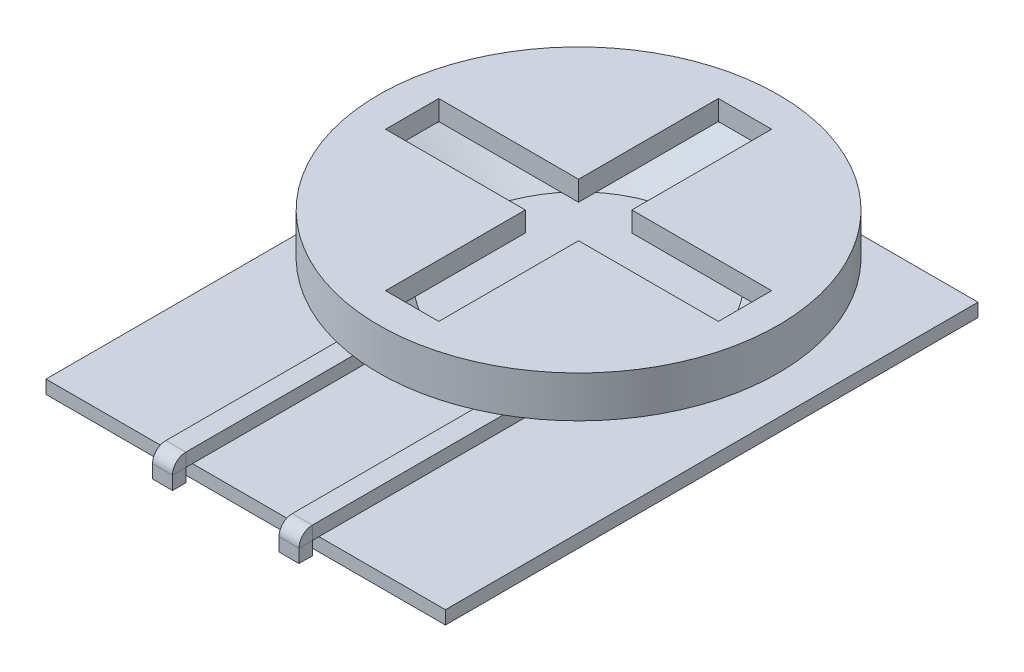
SolidWorks part; units mm, degrees
ref_plane "Front Plane" through (0, 0, 0) normal (0, 0, 1) x (1, 0, 0)
ref_plane "Top Plane" through (0, 0, 0) normal (0, 1, 0) x (1, 0, 0)
ref_plane "Right Plane" through (0, 0, 0) normal (1, 0, 0) x (0, 0, -1)
sketch "Sketch2" plane through (0, 0, 0) normal (0, 1, 0) x (1, 0, 0)
  line L1 (-1.5, 2) -> (1.5, 2)
  line L2 (-1.5, 2) -> (-1.5, -2)
  line L3 (-1.5, -2) -> (1.5, -2)
  line L4 (1.5, 2) -> (1.5, -2)
  line L5 (-1.5, 2) -> (1.5, -2) construction
  line L6 (-1.5, -2) -> (1.5, 2) construction
  point P0 (0, 0)
  dimension "D1" = 4
  dimension "D2" = 3
extrude "Boss-Extrude1" add sketch "Sketch2" along normal blind 0.1
sketch "Sketch4" plane through (0, 0, 0) normal (1, 0, 0) x (0, 0, -1)
  line L0 (0.5, 0.1) -> (0.5, 1.592) construction
  line L1 (-2, 0.1) -> (2, 0.1) construction
  line L2 (2, 0.1) -> (0.5, 0.1) construction
  line L3 (0.5, 0.1) -> (0.5, 0.7)
  line L4 (0.5, 0.7) -> (2, 0.7)
  line L5 (2, 0.7) -> (2, 0.3887)
  line L6 (2, 0.3887) -> (1.5, 0.1)
  line L7 (1.5, 0.1) -> (0.5, 0.1)
  point P9 (2, 0.3519)
  point P11 (1.5306, 0.1)
  point P12 (0.5, 1.592)
  dimension "D1" = 3
  dimension "D2" = 30
  dimension "D3" = 0.6
  dimension "D4" = 1
revolve "Revolve1" add sketch "Sketch4" angle 360 about L0
sketch "Sketch5" plane through (0, 0.7, 0) normal (0, 1, 0) x (1, 0, 0)
  line L0 (0, 0.5) -> (1.5, 0.5) construction
  line L2 (-0.2, 1.75) -> (0.2, 1.75)
  line L3 (-0.2, 1.75) -> (-0.2, -0.75)
  line L4 (-0.2, -0.75) -> (0.2, -0.75)
  line L5 (0.2, 1.75) -> (0.2, -0.75)
  line L6 (-0.2, 1.75) -> (0.2, -0.75) construction
  line L7 (-0.2, -0.75) -> (0.2, 1.75) construction
  line L8 (-1.25, 0.7) -> (1.25, 0.7)
  line L9 (-1.25, 0.7) -> (-1.25, 0.3)
  line L10 (-1.25, 0.3) -> (1.25, 0.3)
  line L11 (1.25, 0.7) -> (1.25, 0.3)
  line L12 (-1.25, 0.7) -> (1.25, 0.3) construction
  line L13 (-1.25, 0.3) -> (1.25, 0.7) construction
  circle A1 centre (0, 0.5) radius 1.5 construction
  circle A2 centre (0, 0.5) radius 1.5
  point P0 (0, 0.5)
  point P5 (0, 0.5)
  point P11 (0.0703, 0.872)
  point P12 (1.5, 0.5)
  point P17 (0.5174, 1.3694)
  point P19 (1.5, 0.5)
  point P20 (0.5911, -0.543)
  point P21 (1.4811, 0.2627)
  point P22 (1.5, 0.5)
  point P23 (0.4161, -0.6669)
  dimension "D1" = 0.4
  dimension "D2" = 2.5
shell "Shell2" thickness 0.15
extrude "Cut-Extrude1" cut sketch "Sketch5" against normal blind 0.15 contours L3 L8 L5 L2 | L3 L10 L5 L8 | L11 L8 L5 L10 | L10 L3 L4 L5 | L9 L10 L3 L8
sketch "Sketch6" plane through (0, 0.1, 0) normal (0, 1, 0) x (1, 0, 0)
  line L0 (0, 0.5) -> (0, -2) construction
  line L1 (-1.5, -2) -> (1.5, -2) construction
  line L2 (-0.55, 0.067) -> (-0.55, -2)
  line L3 (-0.55, -2) -> (-0.4, -2)
  line L4 (-0.4, -2) -> (-0.4, -0.0745)
  line L5 (0.55, 0.067) -> (0.55, -2)
  line L6 (0.55, -2) -> (0.4, -2)
  line L7 (0.4, -2) -> (0.4, -0.0745)
  line L8 (0.475, -2) -> (0.475, -1.8331) construction
  circle A0 centre (0, 0.5) radius 0.7 construction
  arc A1 (0.4, -0.0745) -> (0.55, 0.067) centre (0, 0.5) ccw
  arc A2 (-0.55, 0.067) -> (-0.4, -0.0745) centre (0, 0.5) ccw
  dimension "D1" = 0.15
  dimension "D2" = 0.8
extrude "Boss-Extrude2" add sketch "Sketch6" along normal blind 0.1
sketch "Sketch7" plane through (0, 0.1, 0) normal (0, 1, 0) x (1, 0, 0)
  circle A0 centre (0, 0.5) radius 0.8732
  arc A1 (0.4, -0.2762) -> (0.55, -0.1782) centre (0, 0.5) ccw construction
extrude "Boss-Extrude3" add sketch "Sketch7" along normal blind 0.1
ref_plane "Plane1" through (0.475, 0, 0) normal (1, 0, 0) x (0, 0, -1)
sketch "Sketch8" plane through (0.475, 0, 0) normal (1, 0, 0) x (0, 0, -1)
  line L0 (-2, 0.15) -> (-2.05, 0.15)
  line L1 (-2, 0.2) -> (-2, 0.1) construction
  line L2 (-2.1, 0.1) -> (-2.1, 0)
  line L4 (-2, 0.1) -> (-2, 0) construction
  arc A0 (-2.1, 0.1) -> (-2.05, 0.15) centre (-2.05, 0.1) cw
  point P9 (-2.0744, 0.0308)
  dimension "D2" = 0.1
  dimension "D1" = 0.05
sketch "Sketch9" plane through (0, 0, 2) normal (0, 0, 1) x (1, 0, 0)
  line L4 (0.4, 0.1) -> (0.55, 0.1)
  line L5 (0.55, 0.1) -> (0.55, 0.2)
  line L6 (0.55, 0.2) -> (0.4, 0.2)
  line L7 (0.4, 0.2) -> (0.4, 0.1)
  line L8 (0.4, 0.1) -> (0.55, 0.1)
  line L9 (0.55, 0.1) -> (0.55, 0.2)
  line L10 (0.55, 0.2) -> (0.4, 0.2)
  line L11 (0.4, 0.2) -> (0.4, 0.1)
  dimension "D1" = 0
sweep "Sweep1" add profiles "Sketch9" path "Sketch8"
mirror "Mirror1" about plane through (0, 0, 0) normal (1, 0, 0)
combine bodies "Combine1" operation type add bodies to combine 107 106 105
